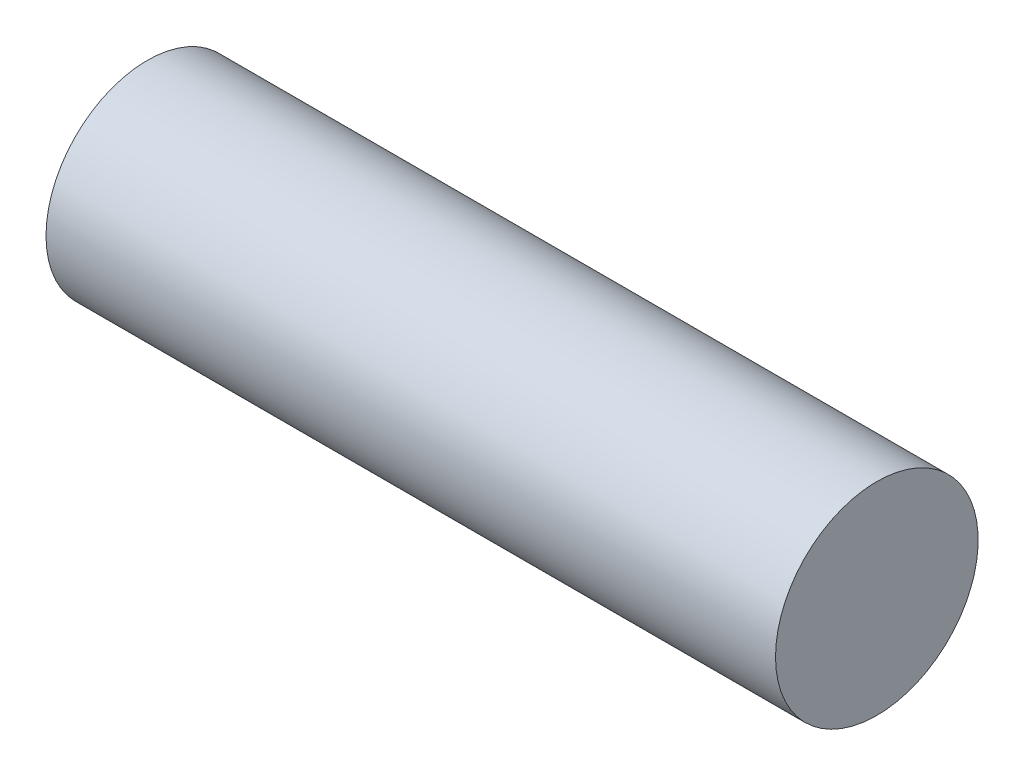
SolidWorks part; units mm, degrees
ref_plane "Front Plane" through (0, 0, 0) normal (0, 0, 1) x (1, 0, 0)
ref_plane "Top Plane" through (0, 0, 0) normal (0, 1, 0) x (1, 0, 0)
ref_plane "Right Plane" through (0, 0, 0) normal (1, 0, 0) x (0, 0, -1)
sketch "Sketch1" plane through (0, 0, 0) normal (1, 0, 0) x (0, 0, -1)
  circle A0 centre (0, 0) radius 6.25
  dimension "D1" = 12.5
extrude "Boss-Extrude1" add sketch "Sketch1" along normal blind 45
